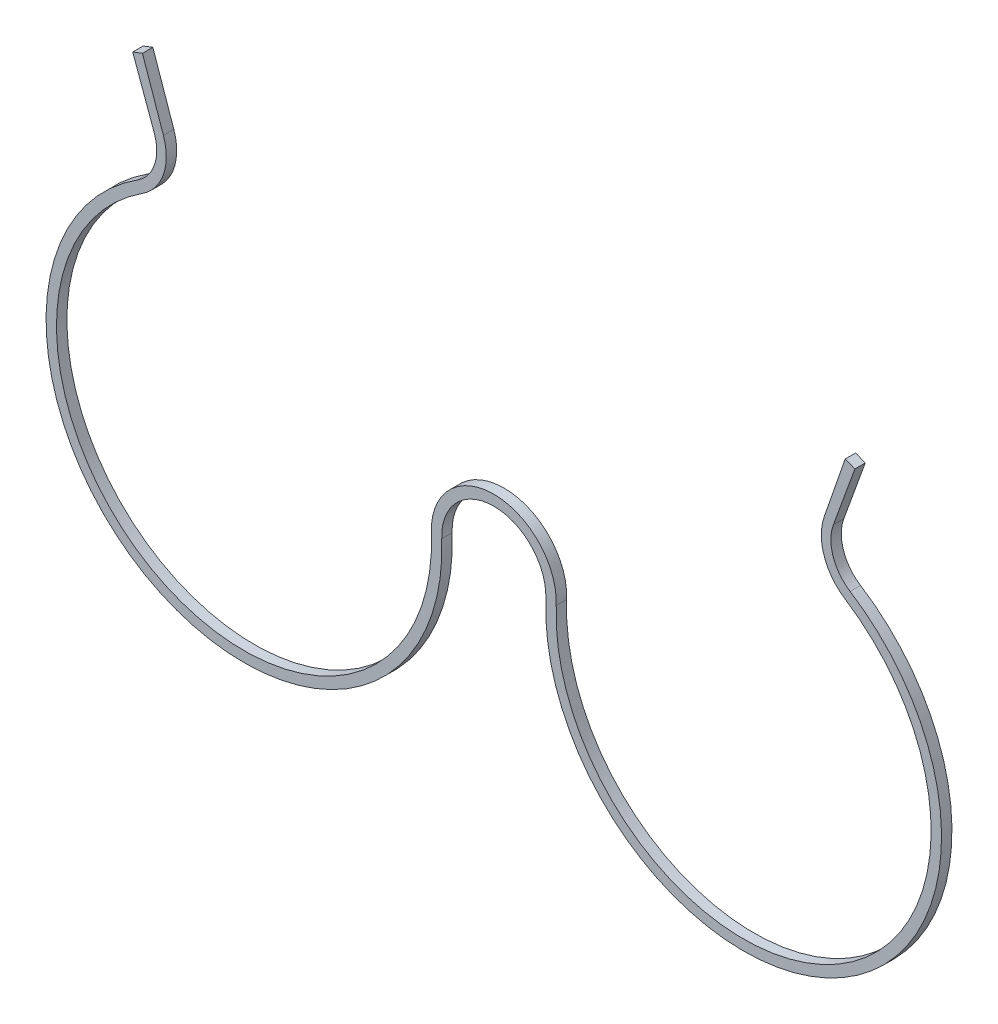
SolidWorks part; units mm, degrees
ref_plane "Plan1" through (0, 0, 0) normal (0, 0, 1) x (1, 0, 0)
ref_plane "Plan2" through (0, 0, 0) normal (0, 1, 0) x (1, 0, 0)
ref_plane "Plan3" through (0, 0, 0) normal (1, 0, 0) x (0, 0, -1)
sketch "Esquisse2" plane through (0, 0, 0) normal (0, 0, 1) x (1, 0, 0)
  line L0 (34.6813, 26.4227) -> (32.618, 20.754)
  line L1 (0.0208, 7) -> (0.0208, 6)
  line L2 (33.7476, 26.7812) -> (31.734, 20.9708)
  arc A0 (6.0156, 0.75) -> (33.75, 15.1307) centre (24, 0) ccw
  arc A1 (6.0156, 0.75) -> (0.0208, 7) centre (0.0208, 1) ccw
  arc A2 (5.0165, 0.7917) -> (-4.9748, 0.7917) centre (0.0208, 1) ccw construction
  arc A3 (34.2243, 16.0145) -> (32.618, 20.754) centre (36.3768, 19.3859) cw
  arc A4 (34.6813, 26.4227) -> (33.7476, 26.7812) centre (24, 0) ccw
  arc A5 (5.0165, 0.7917) -> (34.2243, 16.0145) centre (24, 0) ccw
  arc A6 (5.0165, 0.7917) -> (0.0208, 6) centre (0.0208, 1) ccw
  arc A7 (33.75, 15.1307) -> (31.734, 20.9708) centre (36.4584, 19.3336) cw
  dimension "D2" = 4
  dimension "D3" = 5
  dimension "D1" = 1
extrude "Base-Extrusion" add sketch "Esquisse2" against normal blind 1
mirror "Bossage-Symétrie1" about plane through (0.0208, 7, -1) normal (-1, 0, 0) of bodies 101
